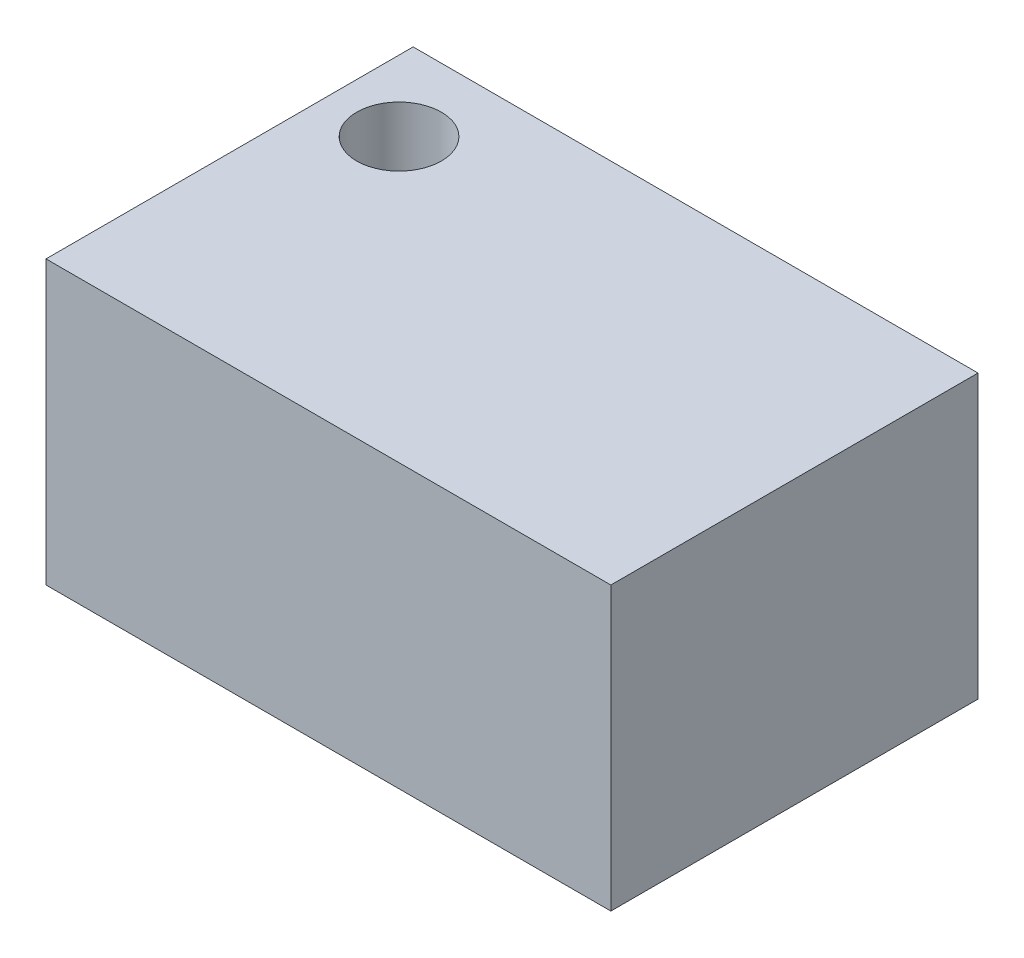
SolidWorks part; units mm, degrees
ref_plane "Plan de face" through (0, 0, 0) normal (0, 0, 1) x (1, 0, 0)
ref_plane "Plan de dessus" through (0, 0, 0) normal (0, 1, 0) x (1, 0, 0)
ref_plane "Plan de droite" through (0, 0, 0) normal (1, 0, 0) x (0, 0, -1)
sketch "Esquisse1" plane through (0, 0, 0) normal (0, 1, 0) x (1, 0, 0)
  line L0 (-10, 6.5) -> (-10, 3.5) construction
  line L1 (-10, -6.5) -> (10, -6.5)
  line L2 (-10, -6.5) -> (-10, 6.5)
  line L3 (-10, 6.5) -> (10, 6.5)
  line L4 (10, -6.5) -> (10, 6.5)
  line L5 (-10, -6.5) -> (10, 6.5) construction
  line L6 (-10, 6.5) -> (10, -6.5) construction
  line L7 (-10, 3.5) -> (-7.5, 3.5) construction
  circle A0 centre (-7.5, 3.5) radius 1.5
  point P0 (0, 0)
  dimension "D1" = 20
  dimension "D2" = 13
extrude "Boss.-Extru.1" add sketch "Esquisse1" along normal blind 10
